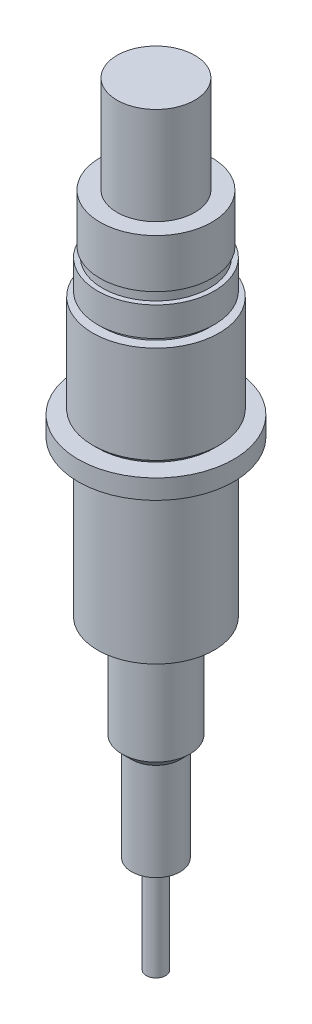
SolidWorks part; units mm, degrees
material "Chrome Stainless Steel"
ref_plane "Front Plane" through (0, 0, 0) normal (0, 0, 1) x (1, 0, 0)
ref_plane "Top Plane" through (0, 0, 0) normal (0, 1, 0) x (1, 0, 0)
ref_plane "Right Plane" through (0, 0, 0) normal (1, 0, 0) x (0, 0, -1)
sketch "Sketch1" plane through (0, 0, 0) normal (1, 0, 0) x (0, 0, -1)
  line L0 (0, 32) -> (0, -47.5)
  line L1 (0, -47.5) -> (1, -47.5)
  line L2 (1, -47.5) -> (1, -37.5)
  line L3 (1, -37.5) -> (2.5, -37.5)
  line L4 (2.5, -37.5) -> (2.5, -27.5)
  line L5 (2.5, -27.5) -> (3.5, -26.5)
  line L6 (3.5, -26.5) -> (3.5, -16.5)
  line L7 (5, 0) -> (8, 0)
  line L8 (8, 0) -> (8, 2)
  line L9 (8, 2) -> (6, 2)
  line L10 (3.5, -16.5) -> (3, -16.5)
  line L11 (3, -16.5) -> (3, -16)
  line L12 (3, -16) -> (6, -16)
  line L13 (6, -16) -> (6, -1)
  line L14 (6, -1) -> (5, 0)
  line L16 (6.5, 12.5) -> (5.5, 12.5)
  line L17 (5.5, 12.5) -> (5.5, 13)
  line L18 (5.5, 13) -> (6, 13)
  line L19 (6, 13) -> (6, 16)
  line L20 (6, 16) -> (5.5, 16)
  line L21 (5.5, 16) -> (5.5, 17)
  line L22 (5.5, 17) -> (5.75, 17)
  line L23 (5.75, 17) -> (5.75, 22)
  line L24 (5.75, 22) -> (4, 22)
  line L25 (4, 22) -> (4, 32)
  line L27 (6, 2) -> (6.5, 2.5)
  line L28 (6.5, 2.5) -> (6.5, 12.5)
  line L29 (0, 32) -> (4, 32)
  dimension "D1" = 1
  dimension "D2" = 6
  dimension "D3" = 8
  dimension "D4" = 10
  dimension "D5" = 10
  dimension "D6" = 10
  dimension "D7" = 45
  dimension "D8" = 1
  dimension "D9" = 0.5
  dimension "D10" = 0.5
  dimension "D11" = 2.5
  dimension "D12" = 45
  dimension "D13" = 5
  dimension "D14" = 2
  dimension "D15" = 6.5
  dimension "D16" = 15
  dimension "D17" = 1
  dimension "D18" = 6
  dimension "D19" = 0.5
  dimension "D20" = 10
  dimension "D21" = 3
  dimension "D22" = 5.5
  dimension "D23" = 1
  dimension "D24" = 5
  dimension "D25" = 5.75
  dimension "D26" = 4
  dimension "D27" = 10
revolve "Revolve1" add sketch "Sketch1" angle 360 about L0
